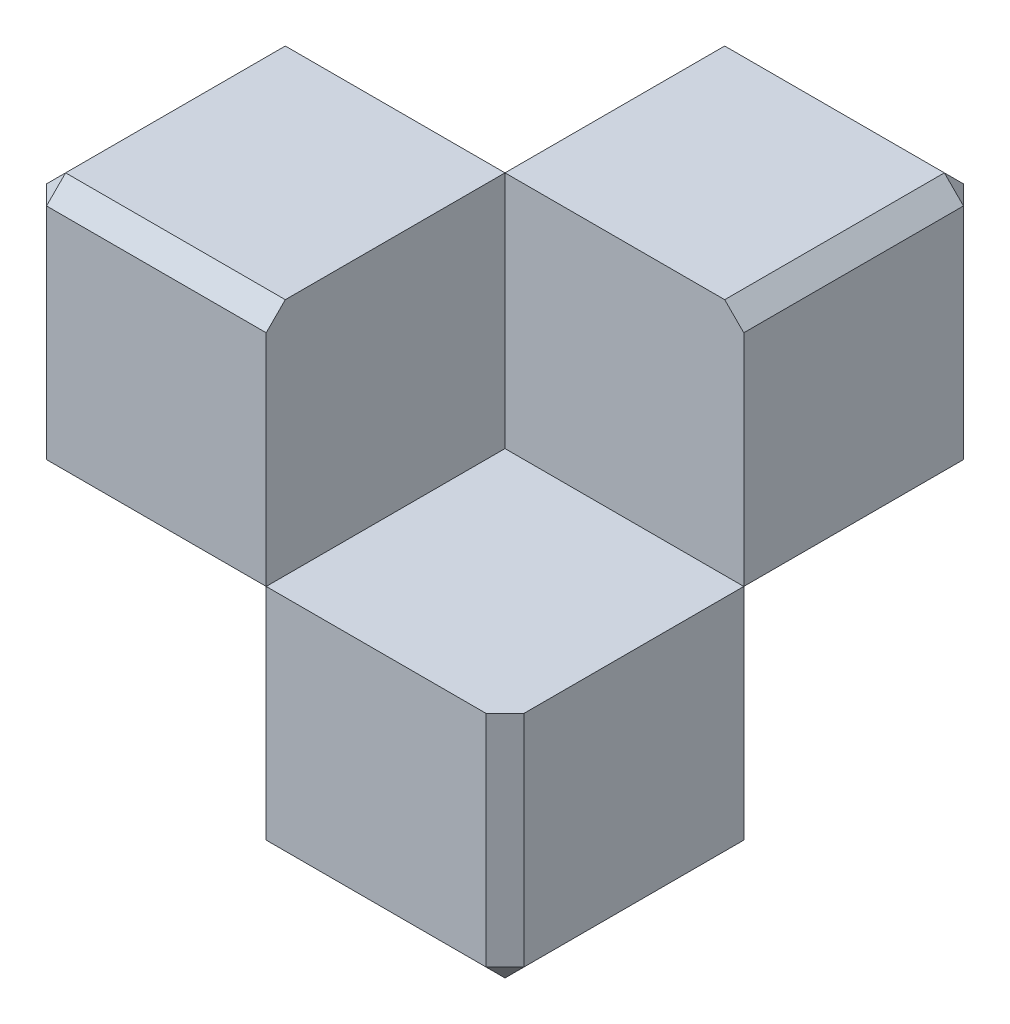
SolidWorks part; units mm, degrees
ref_plane "Front Plane" through (0, 0, 0) normal (0, 0, 1) x (1, 0, 0)
ref_plane "Top Plane" through (0, 0, 0) normal (0, 1, 0) x (1, 0, 0)
ref_plane "Right Plane" through (0, 0, 0) normal (1, 0, 0) x (0, 0, -1)
sketch "Sketch1" plane through (0, 0, 0) normal (0, 0, 1) x (1, 0, 0)
  line L1 (0, 0) -> (-25, 0)
  line L2 (0, 0) -> (0, -25)
  line L3 (0, -25) -> (-25, -25)
  line L4 (-25, 0) -> (-25, -25)
  line L5 (0, 0) -> (25, 0)
  line L6 (0, 0) -> (0, 25)
  line L7 (0, 25) -> (25, 25)
  line L8 (25, 0) -> (25, 25)
  dimension "D1" = 25
extrude "Boss-Extrude1" add sketch "Sketch1" along normal blind 25 contours L1 L4 L3 L2 | L5 L8 L7 L6
sketch "Sketch2" plane through (0, 0, 25) normal (0, 0, 1) x (1, 0, 0)
  line L1 (0, 0) -> (25, 0)
  line L2 (0, 0) -> (0, -25)
  line L3 (0, -25) -> (25, -25)
  line L4 (25, 0) -> (25, -25)
  line L5 (0, 0) -> (-25, 0)
  line L6 (0, 0) -> (0, 25)
  line L7 (0, 25) -> (-25, 25)
  line L8 (-25, 0) -> (-25, 25)
  line L9 (25, 0) -> (25, 25) construction
  line M5 (0, 0) -> (-25, 0)
  line M8 (0, -25) -> (0, 0)
extrude "Boss-Extrude2" add sketch "Sketch2" along normal blind 25 separate body contours L8 L6 L7 M5 | L4 L1 L3 M8
chamfer "Chamfer1" distance 2 angle 45 3 edges at (12.5, 25, 0) (25, 12.5, 0) (25, 25, 12.5)
chamfer "Chamfer2" distance 2 angle 45 3 edges at (-25, 12.5, 50) (-12.5, 25, 50) (-25, 25, 37.5)
chamfer "Chamfer3" distance 2 angle 45 3 edges at (-25, -25, 12.5) (-12.5, -25, 0) (-25, -12.5, 0)
chamfer "Chamfer4" distance 2 angle 45 3 edges at (25, -12.5, 50) (12.5, -25, 50) (25, -25, 37.5)
